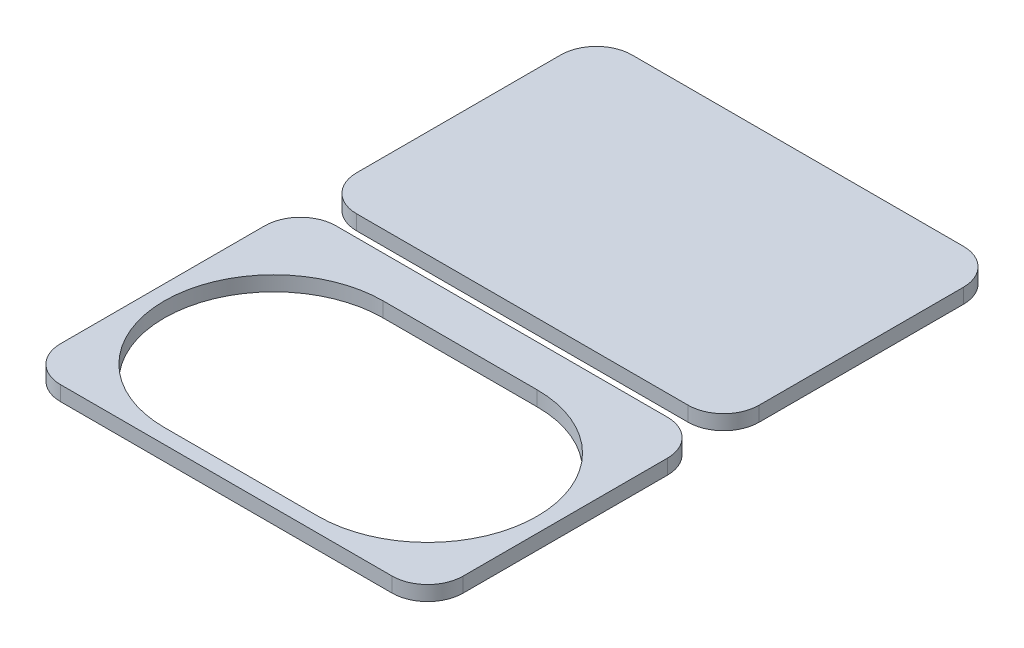
SolidWorks part; units mm, degrees
ref_plane "Front Plane" through (0, 0, 0) normal (0, 0, 1) x (1, 0, 0)
ref_plane "Top Plane" through (0, 0, 0) normal (0, 1, 0) x (1, 0, 0)
ref_plane "Right Plane" through (0, 0, 0) normal (1, 0, 0) x (0, 0, -1)
sketch "Sketch1" plane through (0, 0, 0) normal (0, 1, 0) x (1, 0, 0)
  line L1 (0, 0) -> (136, 0)
  line L2 (0, 0) -> (0, 93)
  line L3 (0, 93) -> (136, 93)
  line L4 (136, 0) -> (136, 93)
  dimension "D1" = 93
  dimension "D2" = 136
extrude "Boss-Extrude1" add sketch "Sketch1" along normal blind 5
fillet "Fillet1" radius 12 4 edges at (0, 2.5, -93) (136, 2.5, -93) (136, 2.5, 0) (0, 2.5, 0)
move or copy body "Body-Move/Copy1" bodies to move or copy 101 copy yes number of copies 1 translate (0, 0, -100)
sketch "Sketch2" plane through (0, 5, 0) normal (0, 1, 0) x (1, 0, 0)
  line L0 (5, 42) -> (0, 42) construction
  line L3 (42, 42) -> (94, 42) construction
  line L4 (42, 79) -> (94, 79)
  line L5 (42, 5) -> (94, 5)
  line L6 (0, 81) -> (0, 12) construction
  line L7 (68, 5) -> (68, 0) construction
  line L8 (12, 0) -> (124, 0) construction
  arc A0 (42, 79) -> (42, 5) centre (42, 42) ccw
  arc A1 (94, 5) -> (94, 79) centre (94, 42) ccw
  point P8 (68, 42)
  point P15 (68, 9.8701)
  point P16 (68, 5)
  dimension "D2" = 37
  dimension "D1" = 52
extrude "Cut-Extrude1" cut sketch "Sketch2" against normal through all
